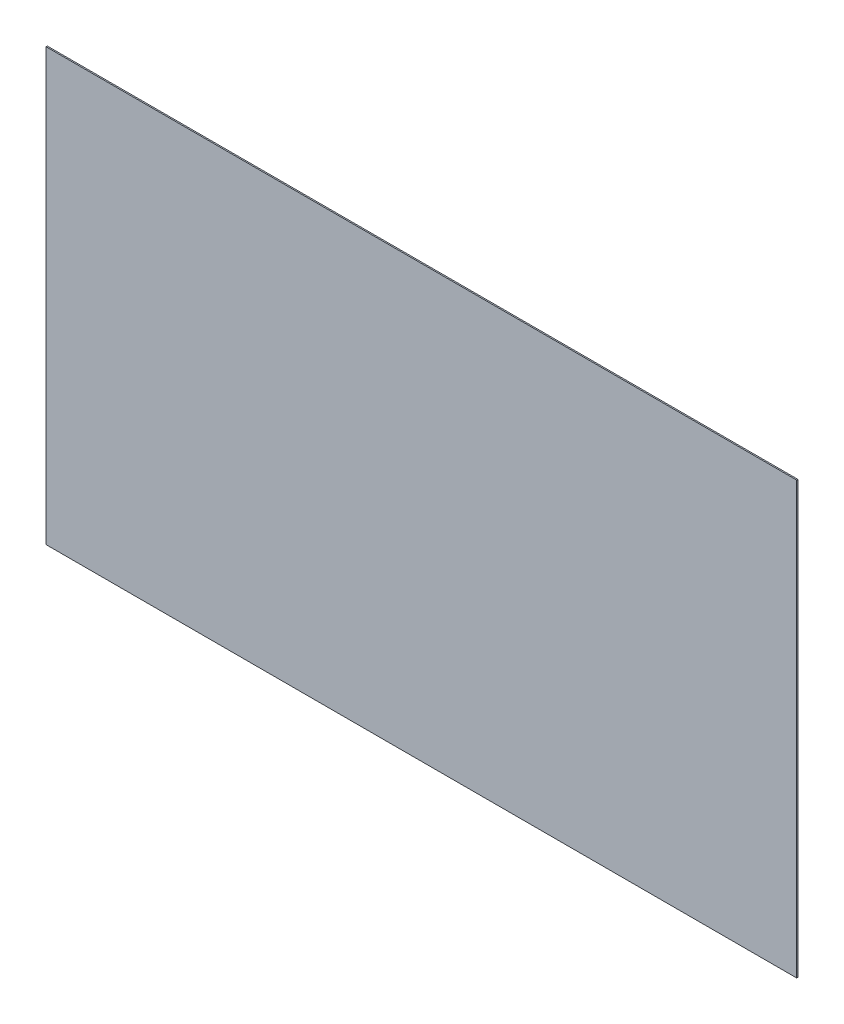
SolidWorks part; units mm, degrees
material "AISI 1020"
ref_plane "Front Plane" through (0, 0, 0) normal (0, 0, 1) x (1, 0, 0)
ref_plane "Top Plane" through (0, 0, 0) normal (0, 1, 0) x (1, 0, 0)
ref_plane "Right Plane" through (0, 0, 0) normal (1, 0, 0) x (0, 0, -1)
sketch "Sketch2" plane through (0, 0, 0) normal (0, 0, 1) x (1, 0, 0)
  line L1 (-298.45, -171.45) -> (298.45, -171.45)
  line L2 (-298.45, -171.45) -> (-298.45, 171.45)
  line L3 (-298.45, 171.45) -> (298.45, 171.45)
  line L4 (298.45, -171.45) -> (298.45, 171.45)
  line L5 (-298.45, -171.45) -> (298.45, 171.45) construction
  line L6 (-298.45, 171.45) -> (298.45, -171.45) construction
  point P0 (0, 0)
  dimension "D1" = 596.9
  dimension "D2" = 342.9
extrude "Boss-Extrude1" add sketch "Sketch2" along normal blind 1
equation "\"A\"= 100"
equation "\"B\"= 100"
equation "\"C\"= 100"
equation "\"D\"= 100"
equation "\"E\"= 100"
